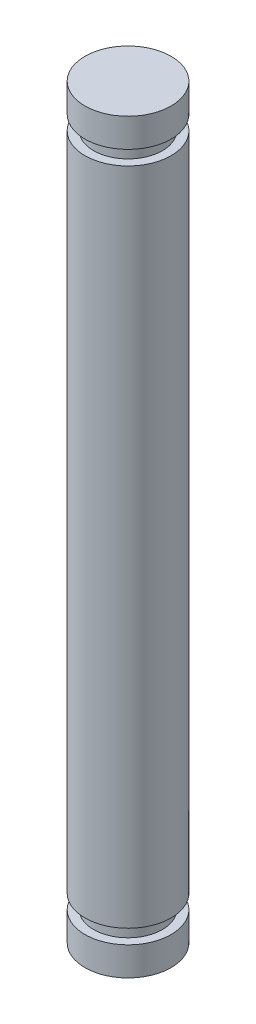
SolidWorks part; units mm, degrees
material "Cast Alloy Steel"
ref_plane "Front" through (0, 0, 0) normal (0, 0, 1) x (1, 0, 0)
ref_plane "Top" through (0, 0, 0) normal (0, 1, 0) x (1, 0, 0)
ref_plane "Right" through (0, 0, 0) normal (1, 0, 0) x (0, 0, -1)
sketch "Sketch1" plane through (0, 0, 0) normal (0, 1, 0) x (1, 0, 0)
  circle A0 centre (0, 0) radius 1.5
  dimension "D1" = 3
extrude "Boss-Extrude1" add sketch "Sketch1" along normal blind 26
sketch "Sketch2" plane through (0, 0, 0) normal (1, 0, 0) x (0, 0, -1)
  line L0 (0, 0) -> (0, 10.4864) construction
  line L1 (-1.5, 0) -> (1.5, 0) construction
  line L2 (-1.2, 1) -> (-3.8976, 1)
  line L3 (-1.2, 1) -> (-1.2, 1.5)
  line L4 (-1.2, 1.5) -> (-3.8976, 1.5)
  line L5 (-3.8976, 1) -> (-3.8976, 1.5)
  line L6 (-1.5, 26) -> (-1.5, 0) construction
  dimension "D1" = 1
  dimension "D2" = 0.5
  dimension "D3" = 0.3
revolve "Cut-Revolve1" cut sketch "Sketch2" angle 360 about L0
ref_plane "Plane1" through (0, 13, 0) normal (0, 1, 0) x (1, 0, 0)
mirror "Mirror1" about plane through (0, 13, 0) normal (0, 1, 0) of "Cut-Revolve1"
